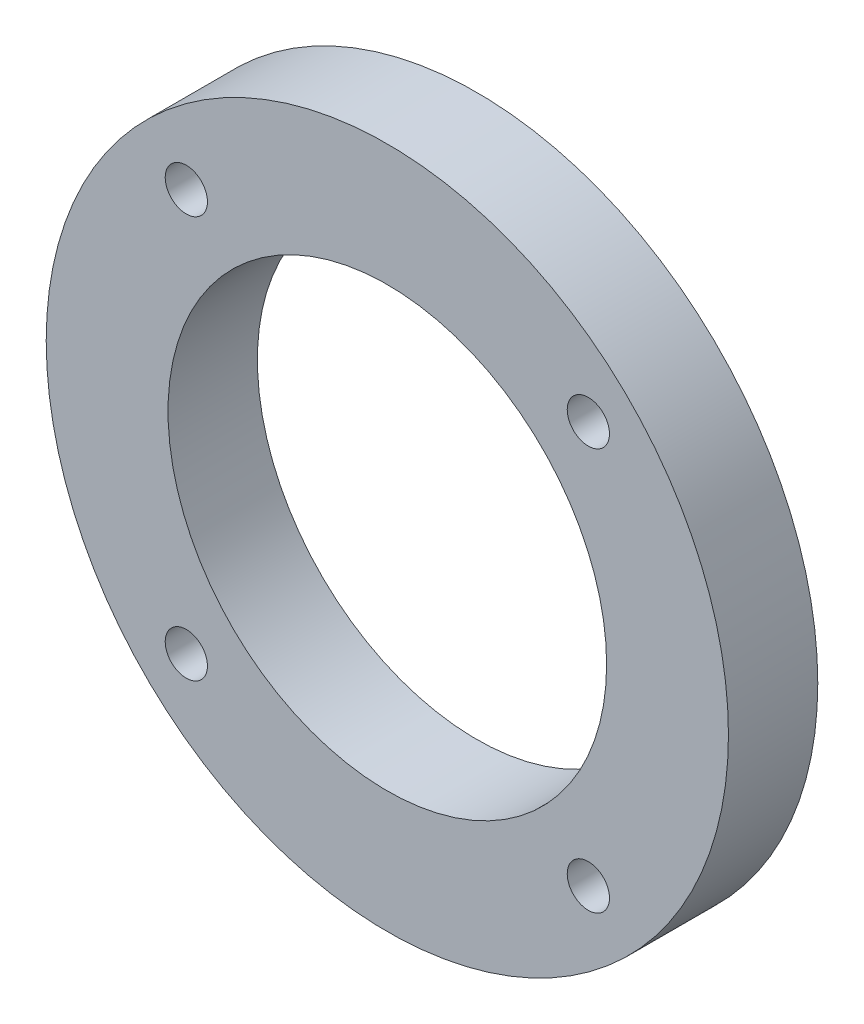
SolidWorks part; units mm, degrees
material "POM 乙缩醛共聚物"
ref_plane "前视基准面" through (0, 0, 0) normal (0, 0, 1) x (1, 0, 0)
ref_plane "上视基准面" through (0, 0, 0) normal (0, 1, 0) x (1, 0, 0)
ref_plane "右视基准面" through (0, 0, 0) normal (1, 0, 0) x (0, 0, -1)
sketch "草图1" plane through (0, 0, 0) normal (0, 0, 1) x (1, 0, 0)
  circle A0 centre (0, 0) radius 13.5
  circle A1 centre (0, 0) radius 21
  dimension "D1" = 27
  dimension "D2" = 42
extrude "凸台-拉伸1" add sketch "草图1" along normal blind 5.5
sketch "草图2" plane through (0, 0, 0) normal (0, 0, -1) x (-1, 0, 0)
  line L1 (12.3744, -12.3744) -> (-12.3744, -12.3744) construction
  line L2 (12.3744, -12.3744) -> (12.3744, 12.3744) construction
  line L3 (12.3744, 12.3744) -> (-12.3744, 12.3744) construction
  line L4 (-12.3744, -12.3744) -> (-12.3744, 12.3744) construction
  line L5 (12.3744, -12.3744) -> (-12.3744, 12.3744) construction
  line L6 (12.3744, 12.3744) -> (-12.3744, -12.3744) construction
  circle A0 centre (-12.3744, 12.3744) radius 1.3
  circle A1 centre (12.3744, 12.3744) radius 1.3
  circle A2 centre (12.3744, -12.3744) radius 1.3
  circle A3 centre (-12.3744, -12.3744) radius 1.3
  point P0 (0, 0)
  dimension "D2" = 2.6
  dimension "D3" = 2.6
  dimension "D4" = 2.6
  dimension "D5" = 2.6
  dimension "D1" = 17.5
extrude "切除-拉伸1" cut sketch "草图2" against normal blind 8
